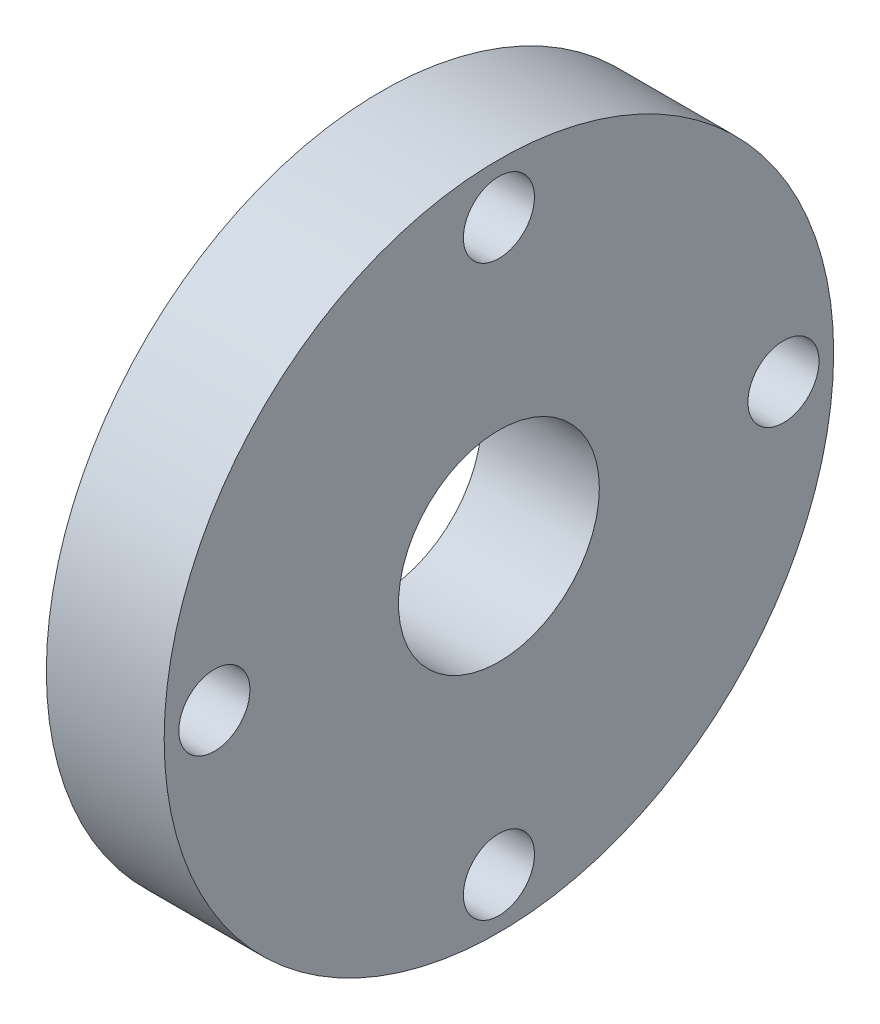
SolidWorks part; units mm, degrees
ref_plane "Front Plane" through (0, 0, 0) normal (1, 0, 0) x (0, 1, 0)
ref_plane "Top Plane" through (0, 0, 0) normal (0, 0, 1) x (0, 1, 0)
ref_plane "Right Plane" through (0, 0, 0) normal (0, 1, 0) x (-1, 0, 0)
sketch "Sketch1" plane through (0, 0, 0) normal (0, 0, 1) x (0, 1, 0)
  line L0 (0, 0) -> (63.5, 0)
  line L1 (63.5, 0) -> (63.5, -22.352)
  line L2 (63.5, -22.352) -> (0, -22.352)
  line L3 (0, -22.352) -> (0, 0)
  line L4 (0, 25.4) -> (0, -47.752) construction
revolve "Revolve1" add sketch "Sketch1" angle 360 about L4
sketch "Sketch2" plane through (0, 0, 0) normal (1, 0, 0) x (0, 1, 0)
  circle A0 centre (0, 0) radius 19.05
extrude "Cut-Extrude2" cut sketch "Sketch2" against normal through all from offset 22.352
sketch "Sketch3" plane through (0, 0, 0) normal (1, 0, 0) x (0, 1, 0)
  circle A0 centre (53.975, 0) radius 4.3688
extrude "Cut-Extrude4" cut sketch "Sketch3" against normal blind 127 from offset 22.352
sketch "Sketch4" plane through (0, 0, 0) normal (1, 0, 0) x (0, 1, 0)
  circle A0 centre (53.975, 0) radius 6.7437
extrude "Cut-Extrude6" cut sketch "Sketch4" against normal blind 9.652 from offset 22.352
sketch "Sketch5" plane through (0, 0, 0) normal (1, 0, 0) x (0, 1, 0)
  circle A0 centre (0, 53.975) radius 4.3688
  circle A1 centre (-53.975, 0) radius 4.3688
  circle A2 centre (0, -53.975) radius 4.3688
extrude "Cut-Extrude8" cut sketch "Sketch5" against normal blind 127 from offset 22.352
sketch "Sketch6" plane through (0, 0, 0) normal (1, 0, 0) x (0, 1, 0)
  circle A0 centre (0, 53.975) radius 6.7437
  circle A1 centre (-53.975, 0) radius 6.7437
  circle A2 centre (0, -53.975) radius 6.7437
extrude "Cut-Extrude10" cut sketch "Sketch6" against normal blind 9.652 from offset 22.352
